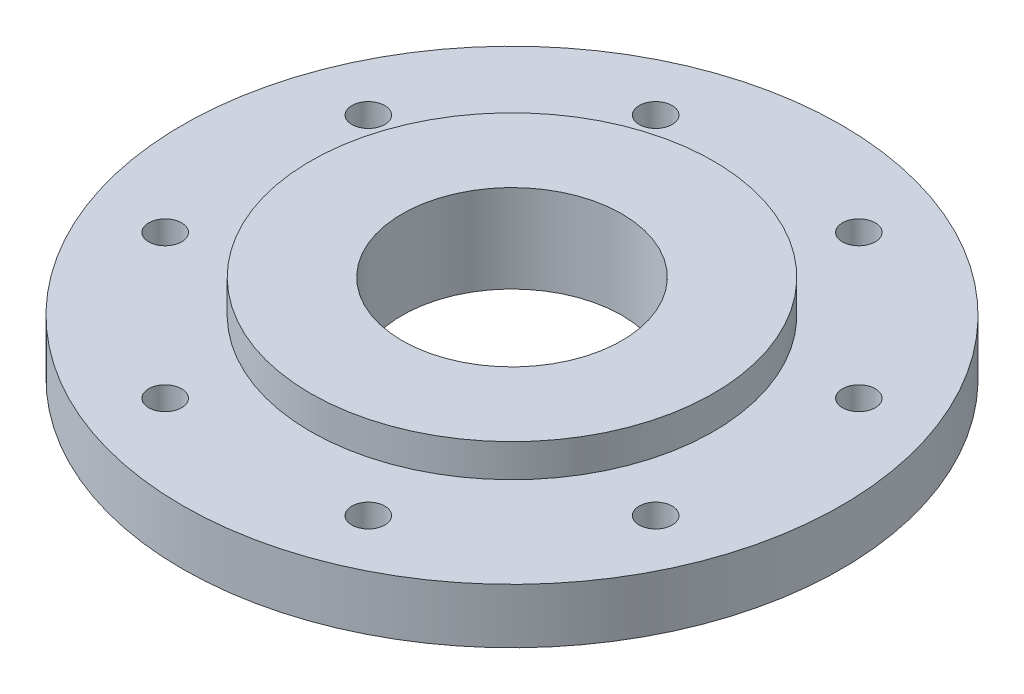
SolidWorks part; units mm, degrees
ref_plane "前视基准面" through (0, 0, 0) normal (0, 0, 1) x (1, 0, 0)
ref_plane "上视基准面" through (0, 0, 0) normal (0, 1, 0) x (1, 0, 0)
ref_plane "右视基准面" through (0, 0, 0) normal (1, 0, 0) x (0, 0, -1)
other "Configuration Table"
sketch "01_Flange_Profile" plane through (0, 0, 0) normal (0, 1, 0) x (1, 0, 0)
  circle A0 centre (0, 0) radius 180
  circle A1 centre (0, 0) radius 60
  circle A2 centre (133.9625, 55.4891) radius 9
  circle A3 centre (55.4891, 133.9625) radius 9
  circle A4 centre (-55.4891, 133.9625) radius 9
  circle A5 centre (-133.9625, 55.4891) radius 9
  circle A6 centre (-133.9625, -55.4891) radius 9
  circle A7 centre (-55.4891, -133.9625) radius 9
  circle A8 centre (55.4891, -133.9625) radius 9
  circle A9 centre (133.9625, -55.4891) radius 9
extrude "01_Flange_Extrude" add sketch "01_Flange_Profile" along normal blind 30
sketch "02_Hub_Profile" plane through (0, 0, 0) normal (0, 1, 0) x (1, 0, 0)
  circle A0 centre (0, 0) radius 110
  circle A1 centre (0, 0) radius 60
extrude "02_Locating_Hub" add sketch "02_Hub_Profile" along normal blind 48
